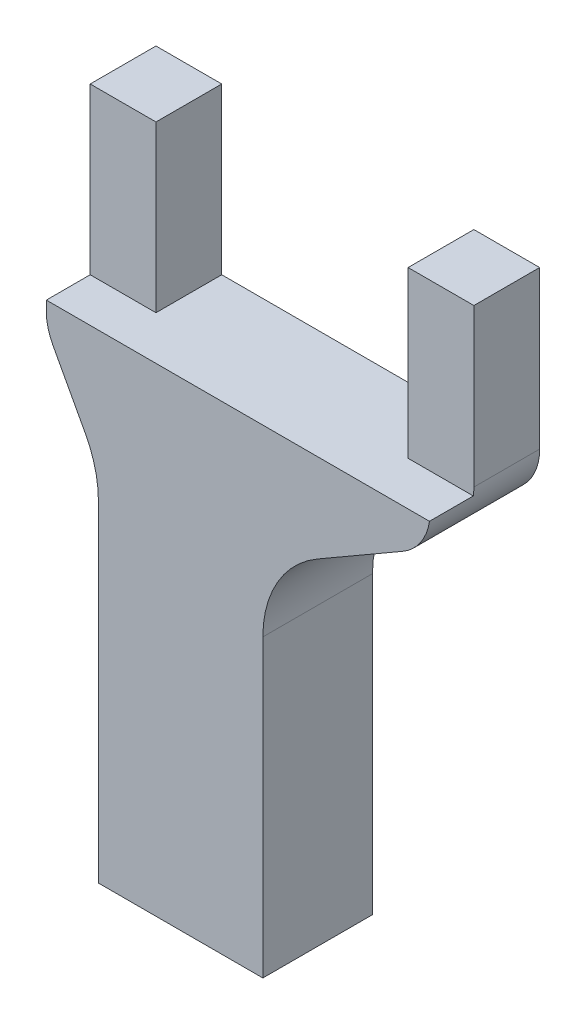
SolidWorks part; units mm, degrees
ref_plane "Front Plane" through (0, 0, 0) normal (0, 0, 1) x (1, 0, 0)
ref_plane "Top Plane" through (0, 0, 0) normal (0, 1, 0) x (1, 0, 0)
ref_plane "Right Plane" through (0, 0, 0) normal (1, 0, 0) x (0, 0, -1)
sketch "Sketch1" plane through (0, 0, 0) normal (0, 0, 1) x (1, 0, 0)
  line L0 (-7.5, 465.3207) -> (-7.5, 488.0002) construction
  line L2 (-7.5, 467.3207) -> (-7.5, 500.038)
  line L3 (-6.25, 511.0002) -> (16.75, 511.0002)
  line L4 (7.5, 467.3207) -> (7.5, 500.038)
  line L5 (7.5, 488.0002) -> (7.5, 465.3207) construction
  line L6 (5.5, 467.3207) -> (-5.5, 467.3207) construction
  line L7 (7.5, 467.3207) -> (-7.5, 467.3207)
  line L9 (-6.25, 526.0712) -> (-6.25, 511.0002)
  line L11 (16.75, 526.0712) -> (16.75, 511.0002)
  line L12 (16.5, 512.5012) -> (16.5, 524.8512) construction
  line L13 (-6, 512.5012) -> (-6, 524.8512) construction
  line L15 (22.75, 526.0712) -> (22.75, 508.8426)
  line L16 (22.75, 508.8426) -> (7.5, 500.038)
  line L17 (16.75, 526.0712) -> (22.75, 526.0712)
  line L18 (-6.25, 526.0712) -> (-12.25, 526.0712)
  line L19 (-12.25, 526.0712) -> (-12.25, 508.8426)
  line L20 (-12.25, 508.8426) -> (-7.5, 500.038)
  circle A0 centre (0, 491.0002) radius 1 construction
  point P1 (-11.6267, 508.8426)
  dimension "D1" = 0
  dimension "D2" = 20
  dimension "D3" = 0.25
  dimension "D4" = 0.25
  dimension "D5" = 6
  dimension "D6" = 6
extrude "Boss-Extrude1" add sketch "Sketch1" along normal blind 10
fillet "Fillet1" radius 10 2 edges at (-7.5, 500.038, 5) (7.5, 500.038, 5)
fillet "Fillet2" radius 5 2 edges at (-12.25, 508.8426, 5) (22.75, 508.8426, 5)
sketch "Sketch2" plane through (0, 0, 10) normal (0, 0, 1) x (1, 0, 0)
  line L0 (16.75, 511.0002) -> (-6.25, 511.0002) construction
  line L1 (-12.25, 526.0712) -> (22.75, 526.0712)
  line L2 (-12.25, 526.0712) -> (-12.25, 511.0002)
  line L3 (-12.25, 511.0002) -> (22.75, 511.0002)
  line L4 (22.75, 526.0712) -> (22.75, 511.0002)
  line L5 (22.75, 511.7293) -> (22.75, 526.0712) construction
  dimension "D1" = 0
  dimension "D2" = 0
extrude "Cut-Extrude1" cut sketch "Sketch2" against normal blind 4
